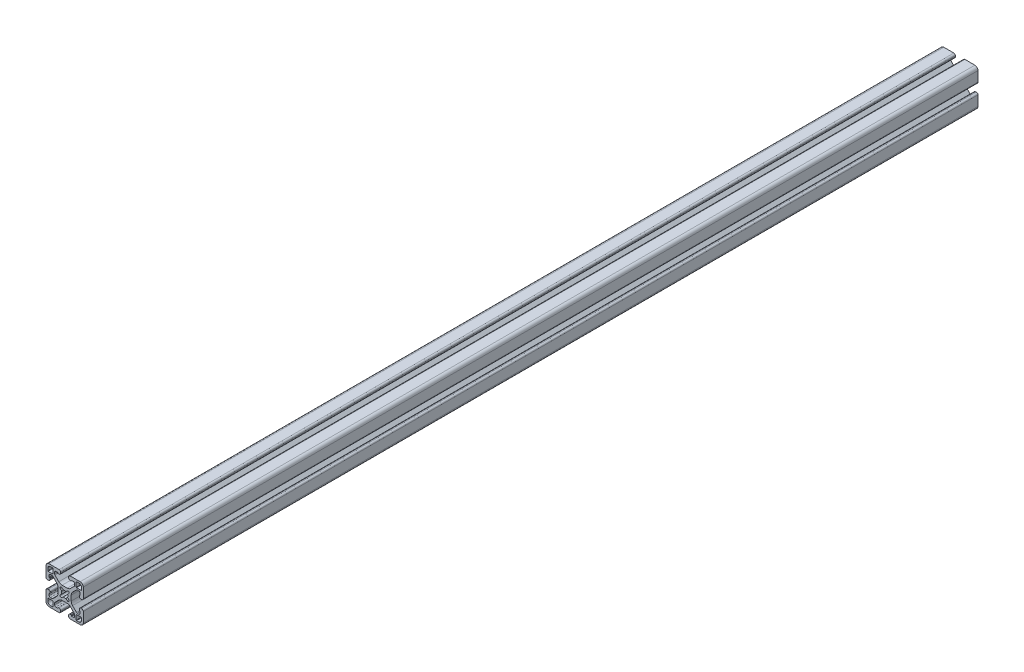
SolidWorks part; units mm, degrees
ref_plane "Front Plane" through (0, 0, 0) normal (0, 0, 1) x (1, 0, 0)
ref_plane "Top Plane" through (0, 0, 0) normal (0, 1, 0) x (1, 0, 0)
ref_plane "Right Plane" through (0, 0, 0) normal (1, 0, 0) x (0, 0, -1)
sketch "Sketch1" plane through (0, 0, 0) normal (0, 0, 1) x (1, 0, 0)
  line L0 (-66.7042, -2.4885) -> (-65.3338, -1.1181)
  line L1 (-65.3338, 1.5948) -> (-66.7042, 2.9652)
  line L2 (-65.0878, 4.5817) -> (-63.7174, 3.2113)
  line L3 (-61.0045, 3.2113) -> (-59.7212, 4.484)
  line L4 (-58.1153, 2.8781) -> (-59.3881, 1.5948)
  line L5 (-59.3881, -1.1181) -> (-58.0176, -2.4885)
  line L6 (-59.6341, -4.1049) -> (-61.0045, -2.7345)
  line L7 (-63.7174, -2.7345) -> (-65.0878, -4.1049)
  line L8 (-79.6075, 12.4812) -> (-79.6075, 14.691)
  line L9 (-76.8135, 17.485) -> (-74.6037, 17.485)
  line L10 (-74.2227, 17.104) -> (-74.2227, 12.4812)
  line L11 (-74.6037, 12.1002) -> (-79.2265, 12.1002)
  line L12 (-74.6037, -17.0082) -> (-76.8135, -17.0082)
  line L13 (-79.6075, -14.2142) -> (-79.6075, -12.0044)
  line L14 (-79.2265, -11.6234) -> (-74.6037, -11.6234)
  line L15 (-74.2227, -12.0044) -> (-74.2227, -16.6272)
  line L16 (-45.1143, -12.0044) -> (-45.1143, -14.2142)
  line L17 (-47.9083, -17.0082) -> (-50.1181, -17.0082)
  line L18 (-50.4991, -16.6272) -> (-50.4991, -12.0044)
  line L19 (-50.1181, -11.6234) -> (-45.4953, -11.6234)
  line L20 (-50.1181, 17.485) -> (-47.9083, 17.485)
  line L21 (-45.1143, 14.691) -> (-45.1143, 12.4812)
  line L22 (-45.4953, 12.1002) -> (-50.1181, 12.1002)
  line L23 (-50.4991, 12.4812) -> (-50.4991, 17.104)
  line L24 (-46.5368, -7.0006) -> (-46.5368, -8.7746)
  line L25 (-47.8067, -10.0486) -> (-49.3926, -10.0486)
  line L26 (-50.2907, -9.6767) -> (-54.2388, -5.7286)
  line L27 (-55.6299, -2.3699) -> (-55.6299, 2.8467)
  line L28 (-54.2388, 6.2053) -> (-50.2907, 10.1534)
  line L29 (-49.3926, 10.5254) -> (-47.8067, 10.5254)
  line L30 (-46.5368, 9.2513) -> (-46.5368, 7.4774)
  line L31 (-46.9178, 7.0964) -> (-46.994, 7.0964)
  line L32 (-47.375, 6.7154) -> (-47.3749, 5.8772)
  line L33 (-45.8001, 4.3024) -> (-44.8857, 4.3024)
  line L34 (-43.3109, 5.8772) -> (-43.3109, 16.1134)
  line L35 (-46.4859, 19.2884) -> (-56.7221, 19.2884)
  line L36 (-58.2969, 17.7136) -> (-58.2969, 16.7992)
  line L37 (-56.7222, 15.2244) -> (-55.884, 15.2244)
  line L38 (-55.503, 15.6054) -> (-55.503, 15.6816)
  line L39 (-55.122, 16.0626) -> (-53.348, 16.0626)
  line L40 (-52.0739, 14.7926) -> (-52.0739, 13.2067)
  line L41 (-52.4459, 12.3087) -> (-56.394, 8.3606)
  line L42 (-59.7526, 6.9694) -> (-64.9693, 6.9694)
  line L43 (-68.3279, 8.3606) -> (-72.276, 12.3087)
  line L44 (-72.6479, 13.2067) -> (-72.6479, 14.7926)
  line L45 (-71.3739, 16.0626) -> (-69.5999, 16.0626)
  line L46 (-69.2189, 15.6816) -> (-69.2189, 15.6054)
  line L47 (-68.8379, 15.2244) -> (-67.9997, 15.2244)
  line L48 (-66.4249, 16.7992) -> (-66.4249, 17.7136)
  line L49 (-67.9997, 19.2884) -> (-78.2359, 19.2884)
  line L50 (-81.4109, 16.1134) -> (-81.4109, 5.8772)
  line L51 (-79.8361, 4.3024) -> (-78.9217, 4.3024)
  line L52 (-77.3469, 5.8772) -> (-77.3469, 6.7154)
  line L53 (-77.7279, 7.0964) -> (-77.8041, 7.0964)
  line L54 (-78.1851, 7.4774) -> (-78.1851, 9.2513)
  line L55 (-76.9151, 10.5254) -> (-75.3293, 10.5254)
  line L56 (-74.4312, 10.1534) -> (-70.4831, 6.2053)
  line L57 (-69.0919, 2.8467) -> (-69.0919, -2.3699)
  line L58 (-70.4831, -5.7286) -> (-74.4312, -9.6767)
  line L59 (-75.3293, -10.0486) -> (-76.9151, -10.0486)
  line L60 (-78.1851, -8.7746) -> (-78.1851, -7.0006)
  line L61 (-77.8041, -6.6196) -> (-77.7279, -6.6196)
  line L62 (-77.3469, -6.2386) -> (-77.3469, -5.4004)
  line L63 (-78.9217, -3.8256) -> (-79.8361, -3.8256)
  line L64 (-81.4109, -5.4004) -> (-81.4109, -15.6366)
  line L65 (-78.2359, -18.8116) -> (-67.9997, -18.8116)
  line L66 (-66.4249, -17.2368) -> (-66.4249, -16.3224)
  line L67 (-67.9997, -14.7476) -> (-68.8379, -14.7476)
  line L68 (-69.2189, -15.1286) -> (-69.2189, -15.2048)
  line L69 (-69.5999, -15.5858) -> (-71.3739, -15.5858)
  line L70 (-72.6479, -14.3158) -> (-72.6479, -12.7299)
  line L71 (-72.276, -11.8319) -> (-68.3279, -7.8838)
  line L72 (-64.9693, -6.4926) -> (-59.7526, -6.4926)
  line L73 (-56.394, -7.8838) -> (-52.4459, -11.8319)
  line L74 (-52.0739, -12.7299) -> (-52.0739, -14.3158)
  line L75 (-53.348, -15.5858) -> (-55.122, -15.5858)
  line L76 (-55.503, -15.2048) -> (-55.503, -15.1286)
  line L77 (-55.884, -14.7476) -> (-56.7222, -14.7476)
  line L78 (-58.2969, -16.3224) -> (-58.2969, -17.2368)
  line L79 (-56.7221, -18.8116) -> (-46.4859, -18.8116)
  line L80 (-43.3109, -15.6366) -> (-43.3109, -5.4004)
  line L81 (-44.8857, -3.8256) -> (-45.8001, -3.8256)
  line L82 (-47.3749, -5.4004) -> (-47.375, -6.2386)
  line L83 (-46.994, -6.6196) -> (-46.9178, -6.6196)
  arc A0 (-66.7042, -2.4885) -> (-65.0878, -4.1049) centre (-65.896, -3.2967) ccw
  arc A1 (-65.3338, 1.5948) -> (-65.3338, -1.1181) centre (-62.3609, 0.2384) ccw
  arc A2 (-65.0878, 4.5817) -> (-66.7042, 2.9652) centre (-65.896, 3.7734) ccw
  arc A3 (-61.0045, 3.2113) -> (-63.7174, 3.2113) centre (-62.3609, 0.2384) ccw
  arc A4 (-58.1153, 2.8781) -> (-59.7212, 4.484) centre (-58.8259, 3.7734) ccw
  arc A5 (-59.3881, -1.1181) -> (-59.3881, 1.5948) centre (-62.3609, 0.2384) ccw
  arc A6 (-59.6341, -4.1049) -> (-58.0176, -2.4885) centre (-58.8259, -3.2967) ccw
  arc A7 (-63.7174, -2.7345) -> (-61.0045, -2.7345) centre (-62.3609, 0.2384) ccw
  arc A8 (-79.6075, 12.4812) -> (-79.2265, 12.1002) centre (-79.2265, 12.4812) ccw
  arc A9 (-76.8135, 17.485) -> (-79.6075, 14.691) centre (-76.8135, 14.691) ccw
  arc A10 (-74.2227, 17.104) -> (-74.6037, 17.485) centre (-74.6037, 17.104) ccw
  arc A11 (-74.6037, 12.1002) -> (-74.2227, 12.4812) centre (-74.6037, 12.4812) ccw
  arc A12 (-74.6037, -17.0082) -> (-74.2227, -16.6272) centre (-74.6037, -16.6272) ccw
  arc A13 (-79.6075, -14.2142) -> (-76.8135, -17.0082) centre (-76.8135, -14.2142) ccw
  arc A14 (-79.2265, -11.6234) -> (-79.6075, -12.0044) centre (-79.2265, -12.0044) ccw
  arc A15 (-74.2227, -12.0044) -> (-74.6037, -11.6234) centre (-74.6037, -12.0044) ccw
  arc A16 (-45.1143, -12.0044) -> (-45.4953, -11.6234) centre (-45.4953, -12.0044) ccw
  arc A17 (-47.9083, -17.0082) -> (-45.1143, -14.2142) centre (-47.9083, -14.2142) ccw
  arc A18 (-50.4991, -16.6272) -> (-50.1181, -17.0082) centre (-50.1181, -16.6272) ccw
  arc A19 (-50.1181, -11.6234) -> (-50.4991, -12.0044) centre (-50.1181, -12.0044) ccw
  arc A20 (-50.1181, 17.485) -> (-50.4991, 17.104) centre (-50.1181, 17.104) ccw
  arc A21 (-45.1143, 14.691) -> (-47.9083, 17.485) centre (-47.9083, 14.691) ccw
  arc A22 (-45.4953, 12.1002) -> (-45.1143, 12.4812) centre (-45.4953, 12.4812) ccw
  arc A23 (-50.4991, 12.4812) -> (-50.1181, 12.1002) centre (-50.1181, 12.4812) ccw
  arc A24 (-47.8067, -10.0486) -> (-46.5368, -8.7746) centre (-47.8067, -8.7786) ccw
  arc A25 (-50.2907, -9.6767) -> (-49.3926, -10.0486) centre (-49.3926, -8.7786) ccw
  arc A26 (-55.6299, -2.3699) -> (-54.2388, -5.7286) centre (-50.8801, -2.3699) ccw
  arc A27 (-54.2388, 6.2053) -> (-55.6299, 2.8467) centre (-50.8801, 2.8467) ccw
  arc A28 (-49.3926, 10.5254) -> (-50.2907, 10.1534) centre (-49.3926, 9.2554) ccw
  arc A29 (-46.5368, 9.2513) -> (-47.8067, 10.5254) centre (-47.8067, 9.2554) ccw
  arc A30 (-46.9178, 7.0964) -> (-46.5368, 7.4774) centre (-46.9178, 7.4774) ccw
  arc A31 (-46.994, 7.0964) -> (-47.375, 6.7154) centre (-46.994, 6.7154) ccw
  arc A32 (-47.3749, 5.8772) -> (-45.8001, 4.3024) centre (-45.8001, 5.8772) ccw
  arc A33 (-44.8857, 4.3024) -> (-43.3109, 5.8772) centre (-44.8857, 5.8772) ccw
  arc A34 (-43.3109, 16.1134) -> (-46.4859, 19.2884) centre (-46.4859, 16.1134) ccw
  arc A35 (-56.7221, 19.2884) -> (-58.2969, 17.7136) centre (-56.7221, 17.7136) ccw
  arc A36 (-58.2969, 16.7992) -> (-56.7222, 15.2244) centre (-56.7221, 16.7992) ccw
  arc A37 (-55.884, 15.2244) -> (-55.503, 15.6054) centre (-55.884, 15.6054) ccw
  arc A38 (-55.122, 16.0626) -> (-55.503, 15.6816) centre (-55.122, 15.6816) ccw
  arc A39 (-52.0739, 14.7926) -> (-53.348, 16.0626) centre (-53.3439, 14.7926) ccw
  arc A40 (-52.4459, 12.3087) -> (-52.0739, 13.2067) centre (-53.3439, 13.2067) ccw
  arc A41 (-59.7526, 6.9694) -> (-56.394, 8.3606) centre (-59.7526, 11.7192) ccw
  arc A42 (-68.3279, 8.3606) -> (-64.9693, 6.9694) centre (-64.9693, 11.7192) ccw
  arc A43 (-72.6479, 13.2067) -> (-72.276, 12.3087) centre (-71.3779, 13.2067) ccw
  arc A44 (-71.3739, 16.0626) -> (-72.6479, 14.7926) centre (-71.3779, 14.7926) ccw
  arc A45 (-69.2189, 15.6816) -> (-69.5999, 16.0626) centre (-69.5999, 15.6816) ccw
  arc A46 (-69.2189, 15.6054) -> (-68.8379, 15.2244) centre (-68.8379, 15.6054) ccw
  arc A47 (-67.9997, 15.2244) -> (-66.4249, 16.7992) centre (-67.9997, 16.7992) ccw
  arc A48 (-66.4249, 17.7136) -> (-67.9997, 19.2884) centre (-67.9997, 17.7136) ccw
  arc A49 (-78.2359, 19.2884) -> (-81.4109, 16.1134) centre (-78.2359, 16.1134) ccw
  arc A50 (-81.4109, 5.8772) -> (-79.8361, 4.3024) centre (-79.8361, 5.8772) ccw
  arc A51 (-78.9217, 4.3024) -> (-77.3469, 5.8772) centre (-78.9217, 5.8772) ccw
  arc A52 (-77.3469, 6.7154) -> (-77.7279, 7.0964) centre (-77.7279, 6.7154) ccw
  arc A53 (-78.1851, 7.4774) -> (-77.8041, 7.0964) centre (-77.8041, 7.4774) ccw
  arc A54 (-76.9151, 10.5254) -> (-78.1851, 9.2513) centre (-76.9151, 9.2554) ccw
  arc A55 (-74.4312, 10.1534) -> (-75.3293, 10.5254) centre (-75.3293, 9.2554) ccw
  arc A56 (-69.0919, 2.8467) -> (-70.4831, 6.2053) centre (-73.8417, 2.8467) ccw
  arc A57 (-70.4831, -5.7286) -> (-69.0919, -2.3699) centre (-73.8417, -2.3699) ccw
  arc A58 (-75.3293, -10.0486) -> (-74.4312, -9.6767) centre (-75.3293, -8.7786) ccw
  arc A59 (-78.1851, -8.7746) -> (-76.9151, -10.0486) centre (-76.9151, -8.7786) ccw
  arc A60 (-77.8041, -6.6196) -> (-78.1851, -7.0006) centre (-77.8041, -7.0006) ccw
  arc A61 (-77.7279, -6.6196) -> (-77.3469, -6.2386) centre (-77.7279, -6.2386) ccw
  arc A62 (-77.3469, -5.4004) -> (-78.9217, -3.8256) centre (-78.9217, -5.4004) ccw
  arc A63 (-79.8361, -3.8256) -> (-81.4109, -5.4004) centre (-79.8361, -5.4004) ccw
  arc A64 (-81.4109, -15.6366) -> (-78.2359, -18.8116) centre (-78.2359, -15.6366) ccw
  arc A65 (-67.9997, -18.8116) -> (-66.4249, -17.2368) centre (-67.9997, -17.2368) ccw
  arc A66 (-66.4249, -16.3224) -> (-67.9997, -14.7476) centre (-67.9997, -16.3224) ccw
  arc A67 (-68.8379, -14.7476) -> (-69.2189, -15.1286) centre (-68.8379, -15.1286) ccw
  arc A68 (-69.5999, -15.5858) -> (-69.2189, -15.2048) centre (-69.5999, -15.2048) ccw
  arc A69 (-72.6479, -14.3158) -> (-71.3739, -15.5858) centre (-71.3779, -14.3158) ccw
  arc A70 (-72.276, -11.8319) -> (-72.6479, -12.7299) centre (-71.3779, -12.7299) ccw
  arc A71 (-64.9693, -6.4926) -> (-68.3279, -7.8838) centre (-64.9693, -11.2424) ccw
  arc A72 (-56.394, -7.8838) -> (-59.7526, -6.4926) centre (-59.7526, -11.2424) ccw
  arc A73 (-52.0739, -12.7299) -> (-52.4459, -11.8319) centre (-53.3439, -12.7299) ccw
  arc A74 (-53.348, -15.5858) -> (-52.0739, -14.3158) centre (-53.3439, -14.3158) ccw
  arc A75 (-55.503, -15.2048) -> (-55.122, -15.5858) centre (-55.122, -15.2048) ccw
  arc A76 (-55.503, -15.1286) -> (-55.884, -14.7476) centre (-55.884, -15.1286) ccw
  arc A77 (-56.7222, -14.7476) -> (-58.2969, -16.3224) centre (-56.7221, -16.3224) ccw
  arc A78 (-58.2969, -17.2368) -> (-56.7221, -18.8116) centre (-56.7221, -17.2368) ccw
  arc A79 (-46.4859, -18.8116) -> (-43.3109, -15.6366) centre (-46.4859, -15.6366) ccw
  arc A80 (-43.3109, -5.4004) -> (-44.8857, -3.8256) centre (-44.8857, -5.4004) ccw
  arc A81 (-45.8001, -3.8256) -> (-47.3749, -5.4004) centre (-45.8001, -5.4004) ccw
  arc A82 (-47.375, -6.2386) -> (-46.994, -6.6196) centre (-46.994, -6.2386) ccw
  arc A83 (-46.5368, -7.0006) -> (-46.9178, -6.6196) centre (-46.9178, -7.0006) ccw
extrude "Extrude1" add sketch "Sketch1" against normal blind 914.4
